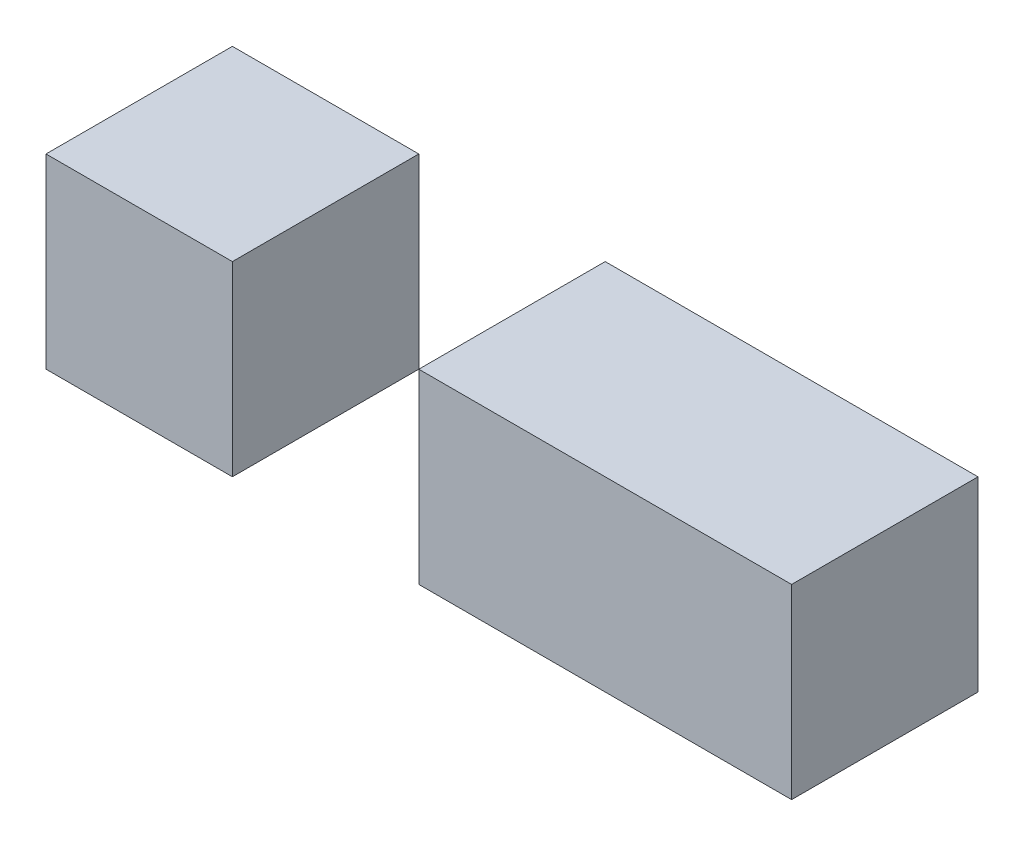
SolidWorks part; units mm, degrees
ref_plane "前视基准面" through (0, 0, 0) normal (0, 0, 1) x (1, 0, 0)
ref_plane "上视基准面" through (0, 0, 0) normal (0, 1, 0) x (1, 0, 0)
ref_plane "右视基准面" through (0, 0, 0) normal (1, 0, 0) x (0, 0, -1)
other "Configuration Table"
sketch "SelectionSeed" plane through (0, 0, 0) normal (0, 0, 1) x (1, 0, 0)
  line L1 (0, 0) -> (10, 0)
  line L2 (0, 0) -> (0, 10)
  line L3 (0, 10) -> (10, 10)
  line L4 (10, 0) -> (10, 10)
  line L6 (20, 0) -> (40, 0)
  line L7 (20, 0) -> (20, 10)
  line L8 (20, 10) -> (40, 10)
  line L9 (40, 0) -> (40, 10)
extrude "SelectionExtrude" add sketch "SelectionSeed" along normal blind 10
